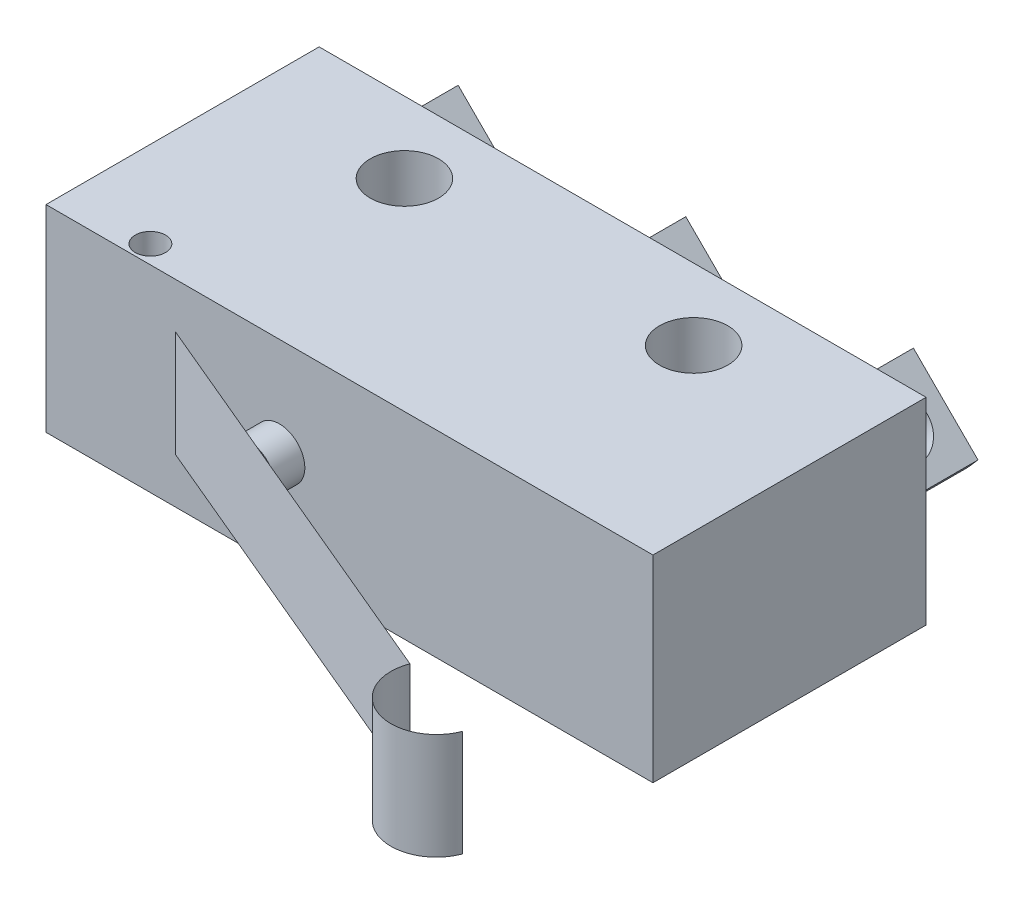
SolidWorks part; units mm, degrees
ref_plane "正面" through (0, 0, 0) normal (0, 0, 1) x (1, 0, 0)
ref_plane "平面" through (0, 0, 0) normal (0, 1, 0) x (1, 0, 0)
ref_plane "右側面" through (0, 0, 0) normal (1, 0, 0) x (0, 0, -1)
sketch "ｽｹｯﾁ1" plane through (0, 0, 0) normal (0, 0, 1) x (1, 0, 0)
  line L1 (-10, -3.25) -> (10, -3.25)
  line L2 (-10, -3.25) -> (-10, 3.25)
  line L3 (-10, 3.25) -> (10, 3.25)
  line L4 (10, -3.25) -> (10, 3.25)
  line L5 (-10, -3.25) -> (10, 3.25) construction
  line L6 (-10, 3.25) -> (10, -3.25) construction
  point P0 (0, 0)
  dimension "D1" = 6.5
  dimension "D2" = 20
extrude "ﾎﾞｽ - 押し出し1" add sketch "ｽｹｯﾁ1" along normal blind 9
hole_wizard "穴1" positions "ｽｹｯﾁ4" profile "ｽｹｯﾁ3" legacy end condition through all
sketch "ｽｹｯﾁ4" plane through (0, -3.25, 0) normal (0, -1, 0) x (-1, 0, 0)
  line L0 (10, -9) -> (10, 0) construction
  line L3 (10, -9) -> (-10, -9) construction
  point P0 (4.84, -2.35)
  point P1 (-4.69, -2.35)
  dimension "D1" = 9.53
  dimension "D2" = 5.16
  dimension "D3" = 6.65
sketch "ｽｹｯﾁ3" plane through (-4.84, -3.25, 2.35) normal (1, 0, 0) x (0, 0, -1)
  line L0 (0, 0) -> (0, 6.5)
  line L1 (0, 6.5) -> (1.125, 6.5)
  line L2 (1.125, 6.5) -> (1.125, 0)
  line L3 (1.125, 0) -> (0, 0)
  line L4 (0, 110) -> (0, -10) construction
  dimension "直径" = 2.25
  dimension "深さ" = 6.5
sketch "ｽｹｯﾁ7" plane through (0, 0, 9) normal (0, 0, 1) x (1, 0, 0)
  line L0 (-5.965, -3.25) -> (-3.715, -3.25) construction
  line L1 (-5.965, -3.25) -> (-3.715, -3.25)
  line L2 (3.565, -3.25) -> (5.815, -3.25) construction
  line L3 (3.565, -3.25) -> (5.815, -3.25)
  line L4 (10, -3.25) -> (10, 3.25)
  line L5 (10, 3.25) -> (-10, 3.25)
  line L6 (-10, 3.25) -> (-10, -3.25)
  line L7 (-10, -3.25) -> (10, -3.25)
  line L8 (10, -3.25) -> (10, 3.25)
  line L9 (10, 3.25) -> (-10, 3.25)
  line L10 (-10, 3.25) -> (-10, -3.25)
  line L11 (-10, -3.25) -> (10, -3.25)
  line L12 (4.69, -3.25) -> (4.69, 3.25) construction
  line L13 (-4.84, -3.25) -> (-4.84, 3.25) construction
  circle A0 centre (-2.31, 0) radius 0.8384
  dimension "D2" = 7
  dimension "D1" = 0
extrude "ﾎﾞｽ - 押し出し2" add sketch "ｽｹｯﾁ7" along normal blind 1 contours A0
hole_wizard "穴2" positions "ｽｹｯﾁ6" profile "ｽｹｯﾁ5" legacy
sketch "ｽｹｯﾁ6" plane through (0, -3.25, 0) normal (0, -1, 0) x (-1, 0, 0)
  line L0 (10, -9) -> (-10, -9) construction
  line L1 (1.4716, -9) -> (3.1484, -9) construction
  line L2 (1.4716, -9) -> (3.1484, -9)
  line L3 (2.31, -9) -> (2.31, 0) construction
  line L4 (10, 0) -> (-10, 0) construction
  point P0 (7.16, -8.4)
  dimension "D1" = 0.6
  dimension "D2" = 4.85
sketch "ｽｹｯﾁ5" plane through (-7.16, -3.25, 8.4) normal (1, 0, 0) x (0, 0, -1)
  line L0 (0, 0) -> (0, 6.5)
  line L1 (0, 6.5) -> (0.5, 6.5)
  line L2 (0.5, 6.5) -> (0.5, 0)
  line L3 (0.5, 0) -> (0, 0)
  line L4 (0, 110) -> (0, -10) construction
  dimension "直径" = 1
  dimension "深さ" = 6.5
ref_plane "平面1" through (0, 0, 0) normal (0, -1, 0) x (-1, 0, 0)
sketch "ｽｹｯﾁ8" plane through (0, 0, 0) normal (0, -1, 0) x (-1, 0, 0)
  line L0 (7.16, -8.4) -> (-7.6006, -14.6078)
  arc A0 (-7.6006, -14.6078) -> (-10.3955, -15.6668) centre (-8.998, -15.1373) cw
  dimension "D1" = 19
surface "ｻｰﾌｪｽ-押し出し1" sketch "ｽｹｯﾁ8" parameters "D1"=3.5
sketch "ｽｹｯﾁ10" plane through (0, 0, 0) normal (0, 0, -1) x (-1, 0, 0)
  line L0 (4.8777, 0) -> (-15.4431, 0) construction
  line L1 (-6.3816, 1.2449) -> (-8.5099, -0.8835)
  line L2 (-6.3816, 1.2449) -> (-6.0586, 0.8632)
  line L3 (-6.0586, 0.8632) -> (-8.1729, -1.2651)
  line L4 (-8.5099, -0.8835) -> (-8.1729, -1.2651)
  line L5 (-6.3816, 1.2449) -> (-8.1729, -1.2651) construction
  line L6 (-6.0586, 0.8632) -> (-8.5099, -0.8835) construction
  line L7 (-10, -3.25) -> (-10, 3.25) construction
  point P0 (-7.27, 0)
  dimension "D1" = 0.5
  dimension "D2" = 3
  dimension "D3" = 2.73
  dimension "D4" = 45
extrude "ﾎﾞｽ - 押し出し3" add sketch "ｽｹｯﾁ10" along normal blind 3.2
hole_wizard "穴3" positions "ｽｹｯﾁ13" profile "ｽｹｯﾁ12" legacy
sketch "ｽｹｯﾁ13" plane through (3.8132, 3.8132, 0) normal (0.7071, 0.7071, 0) x (0, 0, -1)
  line L0 (3.2, -3.6322) -> (3.2, -6.6421) construction
  line L1 (3.2, -3.6322) -> (0, -3.6322) construction
  point P0 (1.7, -5.1322)
  dimension "D1" = 1.5
  dimension "D2" = 1.5
sketch "ｽｹｯﾁ12" plane through (7.4422, 0.1842, -1.7) normal (0, 0, 1) x (-0.7071, 0.7071, 0)
  line L0 (0, 0) -> (0, 6.5)
  line L1 (0, 6.5) -> (0.9, 6.5)
  line L2 (0.9, 6.5) -> (0.9, 0)
  line L3 (0.9, 0) -> (0, 0)
  line L4 (0, 110) -> (0, -10) construction
  dimension "直径" = 1.8
  dimension "深さ" = 6.5
pattern_linear "直線ﾊﾟﾀｰﾝ1" count 3 spacing 7.5 along (-1, 0, 0) of "ﾎﾞｽ - 押し出し3", "穴3"
